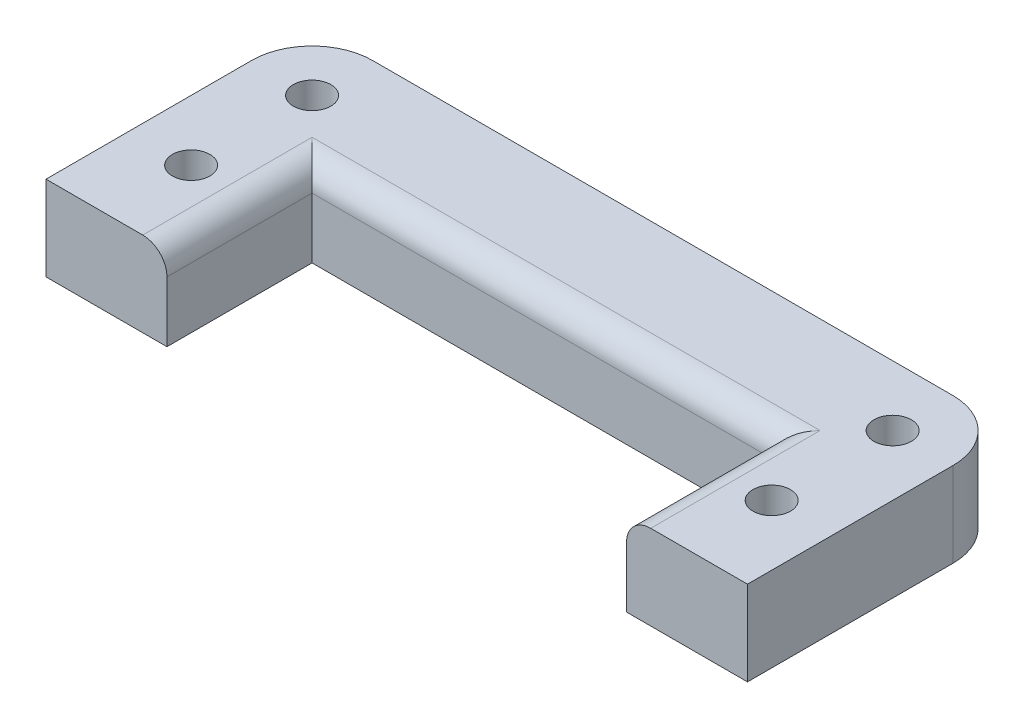
SolidWorks part; units mm, degrees
ref_plane "Alzado" through (0, 0, 0) normal (0, 0, 1) x (1, 0, 0)
ref_plane "Planta" through (0, 0, 0) normal (0, 1, 0) x (1, 0, 0)
ref_plane "Vista lateral" through (0, 0, 0) normal (1, 0, 0) x (0, 0, -1)
sketch "Croquis1" plane through (0, 0, 0) normal (0, 1, 0) x (1, 0, 0)
  line L0 (-29, -7) -> (-29, 15)
  line L1 (-29, 15) -> (29, 15)
  line L2 (29, 15) -> (29, -7)
  line L3 (29, -7) -> (19, -7)
  line L4 (19, -7) -> (19, 5)
  line L5 (19, 5) -> (-19, 5)
  line L6 (-19, 5) -> (-19, -7)
  line L7 (-19, -7) -> (-29, -7)
  line L8 (-24, 0) -> (24, 0) construction
  circle A0 centre (-24, 0) radius 1.55
  circle A1 centre (24, 0) radius 1.55
  circle A2 centre (-24, 10) radius 1.55
  circle A3 centre (24, 10) radius 1.55
  point P2 (0, 5)
  point P14 (0, 0)
  point P19 (-24, -7)
  point P20 (0, 0)
  point P21 (0, 0)
  point P22 (0, 0)
  point P23 (0, 0)
  dimension "D2" = 3.1
  dimension "D3" = 48
  dimension "D5" = 7
  dimension "D8" = 10
  dimension "D1" = 10
  dimension "D4" = 22
  dimension "D6" = 10
  dimension "D7" = 10
extrude "Saliente-Extruir1" add sketch "Croquis1" along normal blind 7
fillet "Redondeo2" radius 2 3 edges at (19, 7, 1) (0, 7, -5) (-19, 7, 1)
fillet "Redondeo3" radius 5 2 edges at (-29, 3.5, -15) (29, 3.5, -15)
